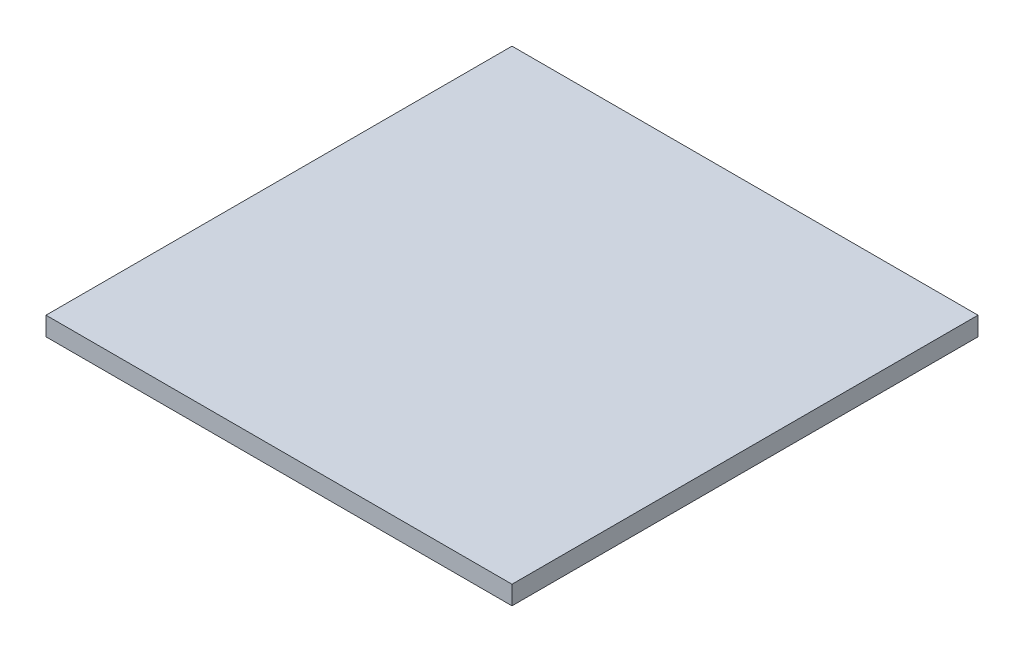
SolidWorks part; units mm, degrees
ref_plane "Front Plane" through (0, 0, 0) normal (0, 0, 1) x (1, 0, 0)
ref_plane "Top Plane" through (0, 0, 0) normal (0, 1, 0) x (1, 0, 0)
ref_plane "Right Plane" through (0, 0, 0) normal (1, 0, 0) x (0, 0, -1)
sketch "Sketch1" plane through (0, 0, 0) normal (0, 0, 1) x (1, 0, 0)
  line L1 (-19.875, -0.8) -> (19.875, -0.8)
  line L2 (-19.875, -0.8) -> (-19.875, 0.8)
  line L3 (-19.875, 0.8) -> (19.875, 0.8)
  line L4 (19.875, -0.8) -> (19.875, 0.8)
  line L5 (-19.875, -0.8) -> (19.875, 0.8) construction
  line L6 (-19.875, 0.8) -> (19.875, -0.8) construction
  point P0 (0, 0)
extrude "Envelope" add sketch "Sketch1" along normal blind 39.75
